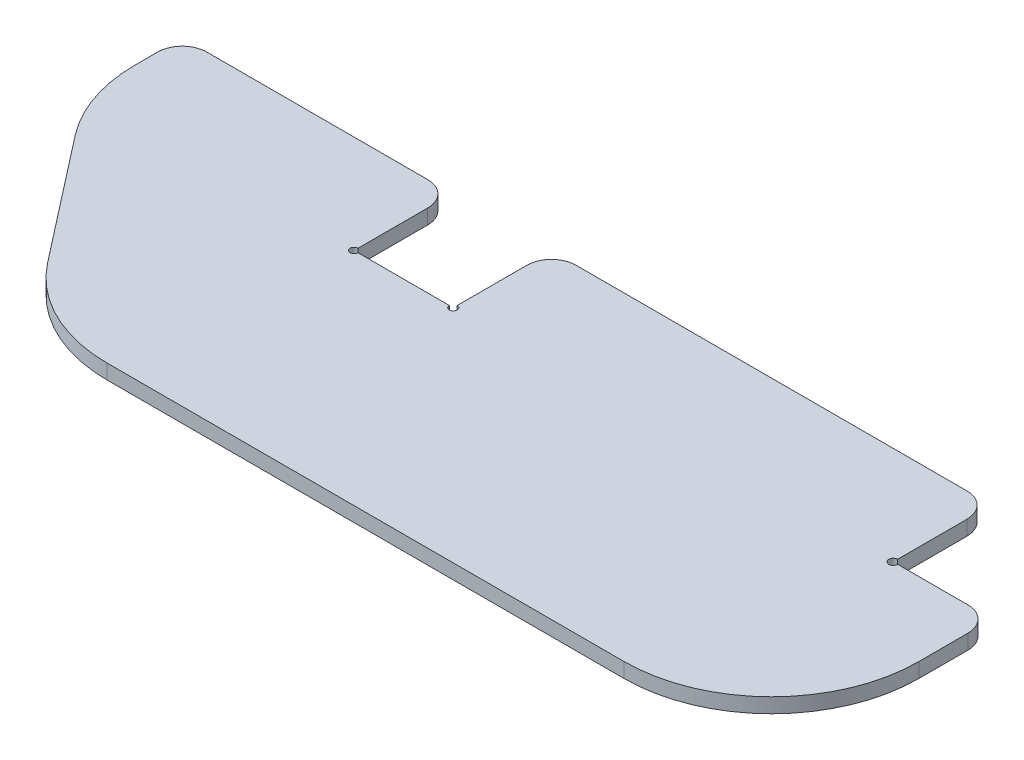
SolidWorks part; units mm, degrees
material "Thornel Mat VMA"
ref_plane "Front Plane" through (0, 0, 0) normal (0, 0, 1) x (1, 0, 0)
ref_plane "Top Plane" through (0, 0, 0) normal (0, 1, 0) x (1, 0, 0)
ref_plane "Right Plane" through (0, 0, 0) normal (1, 0, 0) x (0, 0, -1)
sketch "Sketch1" plane through (0, 0, 0) normal (0, 1, 0) x (1, 0, 0)
  line L1 (-75, -22.5) -> (75, -22.5)
  line L2 (-75, -22.5) -> (-75, 22.5)
  line L3 (-75, 22.5) -> (75, 22.5)
  line L4 (75, -22.5) -> (75, 22.5)
  line L5 (-75, -22.5) -> (75, 22.5) construction
  line L6 (-75, 22.5) -> (75, -22.5) construction
  point P0 (0, 0)
  dimension "D1" = 45
  dimension "D2" = 150
extrude "Boss-Extrude1" add sketch "Sketch1" along normal blind 3
fillet "Fillet1" radius 30 1 edges at (75, 1.5, 22.5)
sketch "Sketch2" plane through (0, 3, 0) normal (0, 1, 0) x (1, 0, 0)
  line L0 (75, 22.5) -> (-75, 22.5) construction
  line L1 (54.8, 22.5) -> (-34.8, 22.5)
  line L2 (54.8, 22.5) -> (54.8, 42.5)
  line L3 (54.8, 42.5) -> (-34.8, 42.5)
  line L4 (-34.8, 22.5) -> (-34.8, 42.5)
  line L5 (75, 7.5) -> (75, 22.5) construction
  line L6 (-110, 22.5) -> (-75, -22.5)
  line L7 (-55, 22.5) -> (-110, 22.5)
  line L8 (-55, 22.5) -> (-55, 42.5)
  line L9 (-55, 42.5) -> (-110, 42.5)
  line L10 (-110, 22.5) -> (-110, 42.5)
  line L11 (-75, -22.5) -> (-75, 22.5)
  line M11 (75, 22.5) -> (-75, 22.5)
  line M12 (-75, 22.5) -> (-75, -22.5)
  dimension "D1" = 89.6
  dimension "D2" = 20.2
  dimension "D3" = 20
  dimension "D4" = 20.2
  dimension "D5" = 35
extrude "Boss-Extrude2" add sketch "Sketch2" against normal up to surface (3 mm away) contours L10 L7 L8 L9 M11 | L7 L6 M12 | L4 L2 L3 M11 up to face at (10.2426, 0, -0.2574)
fillet "Fillet2" radius 30 2 edges at (-75, 1.5, 22.5) (-110, 1.5, -22.5)
sketch "Sketch3" plane through (0, 3, 0) normal (0, 1, 0) x (1, 0, 0)
  circle A0 centre (-55, 22.5) radius 0.8
  circle A1 centre (-34.8, 22.5) radius 0.8
  circle A2 centre (54.8, 22.5) radius 0.8994
  dimension "D1" = 1.6
extrude "Cut-Extrude1" cut sketch "Sketch3" against normal through all
fillet "Fillet3" radius 5 5 edges at (75, 1.5, -22.5) (54.8, 1.5, -42.5) (-34.8, 1.5, -42.5) (-55, 1.5, -42.5) (-110, 1.5, -42.5)
